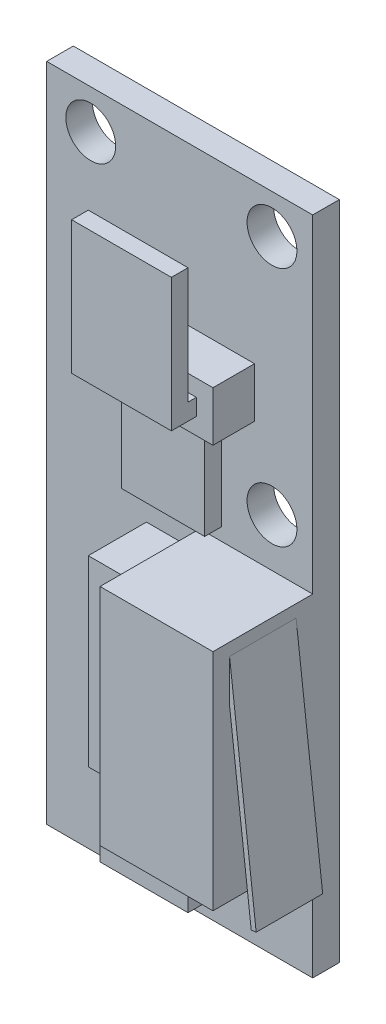
SolidWorks part; units mm, degrees
ref_plane "Alzado" through (0, 0, 0) normal (0, 0, 1) x (1, 0, 0)
ref_plane "Planta" through (0, 0, 0) normal (0, 1, 0) x (1, 0, 0)
ref_plane "Vista lateral" through (0, 0, 0) normal (1, 0, 0) x (0, 0, -1)
sketch "Croquis3" plane through (0, 0, 0) normal (0, 0, 1) x (1, 0, 0)
  line L0 (8, 19.875) -> (-8, -19.875) construction
  line L1 (8, 19.875) -> (-8, 19.875)
  line L2 (8, 19.875) -> (8, -19.875)
  line L3 (8, -19.875) -> (-8, -19.875)
  line L4 (-8, 19.875) -> (-8, -19.875)
  dimension "D1" = 39.75
  dimension "D2" = 16
extrude "Saliente-Extruir1" add sketch "Croquis3" along normal blind 1.6 separate body
sketch "Croquis4" plane through (0, 0, 1.6) normal (0, 0, 1) x (1, 0, 0)
  line L0 (8, -19.875) -> (8, 19.875) construction
  line L1 (2, 5.875) -> (-2, 5.875) construction
  line L2 (2, 5.875) -> (2, 1.375) construction
  line L3 (2, 1.375) -> (-2, 1.375) construction
  line L4 (-2, 5.875) -> (-2, 1.375) construction
  line L5 (1, -14.425) -> (-3.3, -14.425) construction
  line L6 (1, -14.425) -> (1, -18.725) construction
  line L7 (1, -18.725) -> (-3.3, -18.725) construction
  line L8 (-3.3, -14.425) -> (-3.3, -18.725) construction
  line L9 (-8, 19.875) -> (-8, -19.875) construction
  line L10 (-8, -19.875) -> (8, -19.875) construction
  line L11 (8, 19.875) -> (-8, 19.875) construction
  line L12 (2.5, 6.375) -> (-2.5, 6.375)
  line L13 (-2.5, 6.375) -> (-2.5, 0.875)
  line L14 (2.5, 0.875) -> (-2.5, 0.875)
  line L15 (2.5, 6.375) -> (2.5, 0.875)
  line L16 (1.5, -13.925) -> (-3.8, -13.925)
  line L17 (-3.8, -13.925) -> (-3.8, -19.225)
  line L18 (1.5, -19.225) -> (-3.8, -19.225)
  line L19 (1.5, -13.925) -> (1.5, -19.225)
  dimension "D1" = 7
  dimension "D2" = 4.7
  dimension "D3" = 1.15
  dimension "D4" = 4.3
  dimension "D5" = 4
  dimension "D6" = 14
  dimension "D7" = 18.5
  dimension "D8" = 10
  dimension "D9" = 0.5
  dimension "D10" = 0.5
extrude "Saliente-Extruir2" add sketch "Croquis4" along normal blind 1
sketch "Croquis5" plane through (0, 0, 1.6) normal (0, 0, 1) x (1, 0, 0)
  line L0 (8, -19.875) -> (8, 19.875) construction
  line L1 (8, 0.125) -> (1.2079, 0.125)
  line L2 (8, 0.125) -> (8, -13.375)
  line L3 (8, -13.375) -> (1.2079, -13.375)
  line L4 (1.2079, 0.125) -> (1.2079, -13.375)
  line L5 (-8, -19.875) -> (8, -19.875) construction
  dimension "D1" = 6.7921
  dimension "D2" = 20
  dimension "D3" = 13.5
extrude "Saliente-Extruir3" add sketch "Croquis5" along normal blind 6
sketch "Croquis6" plane through (0, 0, 1.6) normal (0, 0, 1) x (1, 0, 0)
  line L0 (1.2079, 0.125) -> (1.2079, -13.375) construction
  line L1 (1.2079, -1.125) -> (-2, -1.125)
  line L2 (1.2079, -1.125) -> (1.2079, -12.125)
  line L3 (1.2079, -12.125) -> (-2, -12.125)
  line L4 (-2, -1.125) -> (-2, -12.125)
  line L5 (8, -6.625) -> (1.2079, -6.625) construction
  line L6 (8, -13.375) -> (8, 0.125) construction
  line L8 (1.2079, 0.125) -> (1.2079, -13.375) construction
  dimension "D1" = 11
  dimension "D2" = 10
extrude "Saliente-Extruir4" add sketch "Croquis6" along normal blind 3.5
sketch "Croquis7" plane through (0, 0, 1.6) normal (0, 0, 1) x (1, 0, 0)
  line L0 (-8, 19.875) -> (-8, -19.875) construction
  line L1 (-3.5, 10.375) -> (4.5, 10.375)
  line L2 (-3.5, 10.375) -> (-3.5, 7.375)
  line L3 (-3.5, 7.375) -> (4.5, 7.375)
  line L4 (4.5, 10.375) -> (4.5, 7.375)
  line L5 (8, 19.875) -> (-8, 19.875) construction
  dimension "D1" = 3
  dimension "D2" = 4.5
  dimension "D3" = 8
  dimension "D4" = 12.5
extrude "Saliente-Extruir5" add sketch "Croquis7" along normal blind 2.5
ref_plane "Plano1" through (0.5, 0, 0) normal (-1, 0, 0) x (0, 0, 1)
sketch "Croquis8" plane through (0.5, 0, 0) normal (-1, 0, 0) x (0, 0, 1)
  line L0 (4.1, 9.375) -> (4.6, 9.375)
  line L1 (4.1, 10.375) -> (4.1, 7.375) construction
  line L2 (4.6, 9.375) -> (4.6, 16.375)
  line L3 (4.6, 16.375) -> (5.6, 16.375)
  line L4 (5.6, 16.375) -> (5.6, 8.375)
  line L5 (5.6, 8.375) -> (4.1, 8.375)
  line L6 (4.1, 8.375) -> (4.1, 9.375)
  line L7 (1.6, 8.875) -> (6.9095, 8.875) construction
  line L8 (1.6, 10.375) -> (1.6, 7.375) construction
  line L9 (1.6, 19.875) -> (1.6, -19.875) construction
  line L10 (4.1, 7.375) -> (1.6, 7.375) construction
  dimension "D1" = 1
  dimension "D2" = 1
  dimension "D3" = 4
  dimension "D4" = 9
extrude "Saliente-Extruir6" add sketch "Croquis8" along normal mid plane 6
sketch "Croquis9" plane through (0, 0, 1.6) normal (0, 0, 1) x (1, 0, 0)
  line L0 (8, 0.125) -> (8, 19.875) construction
  line L1 (8, 19.875) -> (-8, 19.875) construction
  line L2 (-8, 19.875) -> (-8, -19.875) construction
  circle A0 centre (5.55, 17.525) radius 1.5
  circle A1 centre (-5.35, 17.525) radius 1.5
  circle A2 centre (5.55, 3.025) radius 1.5
  circle A3 centre (5.55, -15.925) radius 1.5
  dimension "D1" = 3
  dimension "D2" = 0.95
  dimension "D3" = 0.85
  dimension "D4" = 1.15
  dimension "D5" = 11.5
  dimension "D6" = 15.95
extrude "Cortar-Extruir1" cut sketch "Croquis9" against normal through all
ref_plane "Plano2" through (8, -13.375, 4.6) normal (0, 0, -1) x (-1, 0, 0)
sketch "Croquis10" plane through (8, -13.375, 4.6) normal (0, 0, -1) x (-1, 0, 0)
  line L0 (0, 12.75) -> (-1.6, -0.8149)
  line L1 (0, 0) -> (0, 13.5) construction
  line L2 (-1.6, -0.8149) -> (-1.3021, -0.85)
  line L3 (-1.3021, -0.85) -> (0, 10.189)
  line L4 (0, 10.189) -> (0, 12.75)
  line L5 (0, 13.5) -> (0, 33.25) construction
  line L6 (0, 13.5) -> (6.7921, 13.5) construction
  dimension "D1" = 13.6
  dimension "D2" = 0.3
  dimension "D3" = 1.6
  dimension "D4" = 0.75
extrude "Saliente-Extruir7" add sketch "Croquis10" along normal mid plane 4
sketch "Croquis11" plane through (0, 0, 0) normal (0, 0, -1) x (-1, 0, 0)
  line L0 (-8, -19.875) -> (-8, 19.875) construction
  line L1 (-3.5, 10.875) -> (3.5, 10.875)
  line L2 (-3.5, 10.875) -> (-3.5, 6.875)
  line L3 (-3.5, 6.875) -> (3.5, 6.875)
  line L4 (3.5, 10.875) -> (3.5, 6.875)
  line L5 (-1, -0.625) -> (3, -0.625)
  line L6 (-1, -0.625) -> (-1, -12.625)
  line L7 (-1, -12.625) -> (3, -12.625)
  line L8 (3, -0.625) -> (3, -12.625)
  line L9 (-8, 19.875) -> (8, 19.875) construction
  dimension "D1" = 11.5
  dimension "D2" = 13
  dimension "D3" = 7
  dimension "D4" = 4
  dimension "D5" = 32.5
  dimension "D6" = 12
  dimension "D7" = 11
  dimension "D8" = 4
extrude "Saliente-Extruir8" add sketch "Croquis11" along normal blind 1.5
sketch "Croquis12" [suppressed] plane through (8, 0, 0) normal (1, 0, 0) x (0, 0, -1)
  line L0 (-1.6, 0.125) -> (-1.6, -13.375)
  line L1 (-1.6, -13.375) -> (-7.6, -13.375)
  line L2 (-7.6, -13.375) -> (-7.6, 0.125)
  line L3 (-7.6, 0.125) -> (-1.6, 0.125)
extrude "Saliente-Extruir9" [suppressed] add sketch "Croquis12" along normal blind 0.001
